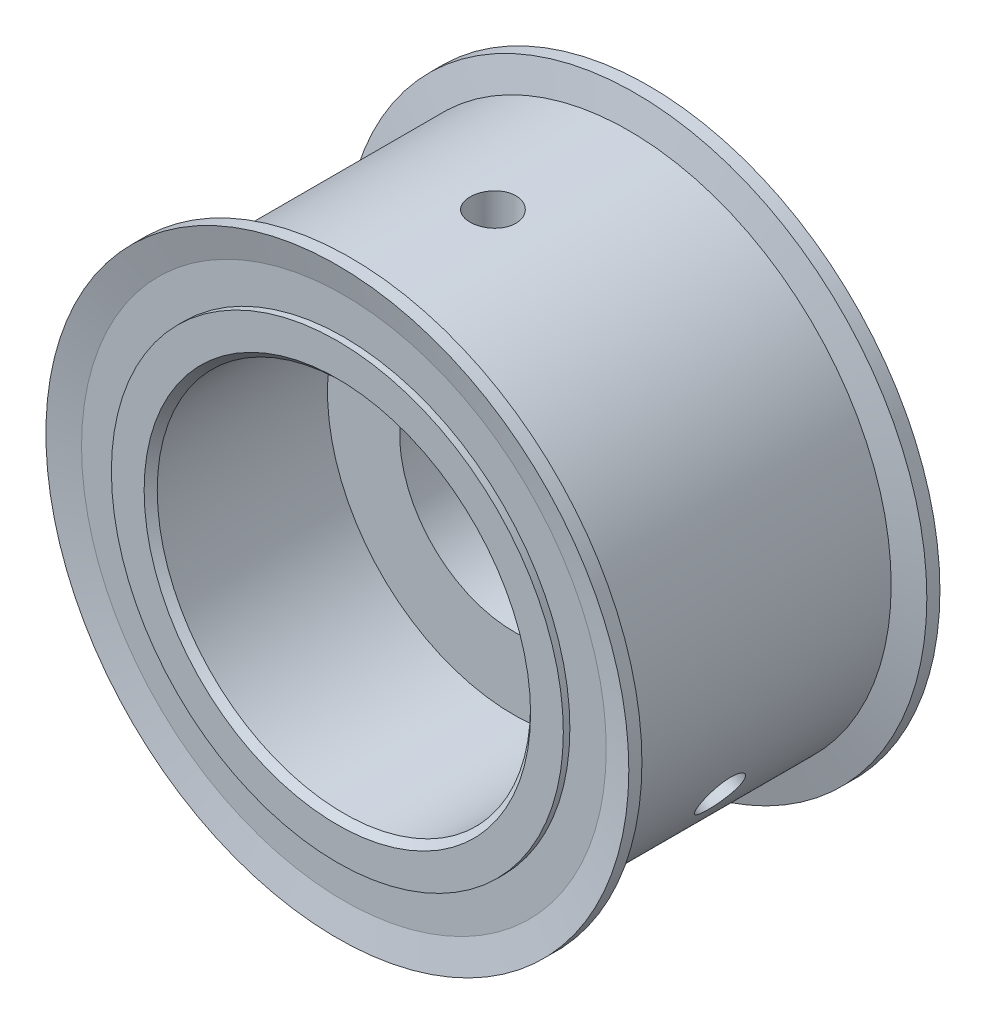
SolidWorks part; units mm, degrees
ref_plane "Front" through (0, 0, 0) normal (0, 0, 1) x (1, 0, 0)
ref_plane "Top" through (0, 0, 0) normal (0, 1, 0) x (1, 0, 0)
ref_plane "Right" through (0, 0, 0) normal (1, 0, 0) x (0, 0, -1)
sketch "Sketch1" plane through (0, 0, 0) normal (1, 0, 0) x (0, 0, -1)
  line L0 (-58.9307, 0) -> (11.953, 0) construction
  line L1 (-47.5, 34.5) -> (-46.5, 34.5)
  line L2 (-47.5, 34.5) -> (-47.5, 0)
  line L3 (-47.5, 0) -> (0, 0)
  line L4 (-1, 34.5) -> (0, 34.5)
  line L5 (-46.5, 34.5) -> (-46.5, 40.055)
  line L6 (-46.5, 40.055) -> (-47.5, 44.5)
  line L7 (-47.5, 44.5) -> (-45.5, 44.5)
  line L8 (-45.5, 44.5) -> (-44.5, 40.055)
  line L9 (-44.5, 40.055) -> (-3, 40.055)
  line L10 (-3, 40.055) -> (-2, 44.5)
  line L11 (-2, 44.5) -> (0, 44.5)
  line L12 (0, 44.5) -> (-1, 40.055)
  line L13 (-1, 40.055) -> (-1, 34.5)
  line L14 (0, 34.5) -> (0, 0)
  dimension "D1" = 69
  dimension "D2" = 80.11
  dimension "D3" = 89
  dimension "D4" = 47.5
  dimension "D5" = 2
  dimension "D6" = 3
revolve "Revolve1" add sketch "Sketch1" angle 360 about L0
sketch "Sketch2" plane through (0, 0, 0) normal (1, 0, 0) x (0, 0, -1)
  line L0 (-2.9836, 0) -> (51.6866, 0) construction
  line L1 (-47.5, 44.5) -> (-47.5, -44.5) construction
  line L2 (-20.5, 17.5) -> (0, 17.5)
  line L3 (-47.5, 28.5) -> (-47.5, 0)
  line L4 (-47.5, 0) -> (0, 0)
  line L5 (0, 17.5) -> (0, 0)
  line L6 (0, 44.5) -> (0, -44.5) construction
  line L7 (-20.5, 17.5) -> (-20.5, 28.5)
  line L8 (-20.5, 28.5) -> (-47.5, 28.5)
  dimension "D1" = 35
  dimension "D2" = 20.5
  dimension "D3" = 57
revolve "Cut-Revolve1" cut sketch "Sketch2" angle 360 about L0
ref_plane "Plane1" through (0, 40.055, 0) normal (0, 1, 0) x (-1, 0, 0)
hole_wizard "Ø7.0 (7) Diameter Hole1" positions "Sketch5" profile "Sketch4" hole size "Ø7.0" standard "JIS"
sketch "Sketch5" plane through (0, 40.055, 0) normal (0, 1, 0) x (-1, 0, 0)
  line L2 (-44.5, 0) -> (44.5, 0) construction
  point P1 (0, 23.75)
  dimension "D1" = 23.75
sketch "Sketch4" plane through (0, 40.055, 23.75) normal (1, 0, 0) x (0, 0, 1)
  line L0 (0, 0) -> (0, 10)
  line L1 (0, 10) -> (3.5, 10)
  line L2 (3.5, 10) -> (3.5, 0)
  line L5 (3.5, 0) -> (0, 0)
  line L10 (0, 10) -> (-3.5, 10) construction
  line L11 (0, -6.35) -> (0, 107.95) construction
  dimension "Hole Dia." = 7
  dimension "Hole Depth" = 10
  dimension "Drill Angle" = 180
hole_wizard "M6x1.0 Tapped Hole1" positions "Sketch7" profile "Sketch6" tap size "M6x1.0" standard "JIS"
sketch "Sketch7" plane through (0, 30.055, 0) normal (0, 1, 0) x (-1, 0, 0)
  point P0 (0, 23.75)
cosmetic thread "Hole Thread1" parameters "D2"=6
sketch "Sketch6" plane through (0, 30.055, 23.75) normal (1, 0, 0) x (0, 0, 1)
  line L0 (0, 0) -> (0, 70.11)
  line L1 (0, 70.11) -> (2.5, 70.11)
  line L2 (2.5, 70.11) -> (2.5, 0)
  line L5 (2.5, 0) -> (0, 0)
  line L11 (0, -6.35) -> (0, 107.95) construction
  dimension "Thru Tap Drill Dia." = 5
  dimension "Thru Tap Drill Depth" = 70.11
pattern_circular "CirPattern1" count 2 over 120 about axis through (0, 0, 2.9836) along (0, 0, 1) of "Ø7.0 (7) Diameter Hole1", "M6x1.0 Tapped Hole1"
chamfer "Chamfer1" distance 1 1 edges at (28.5, 0, 47.5)
